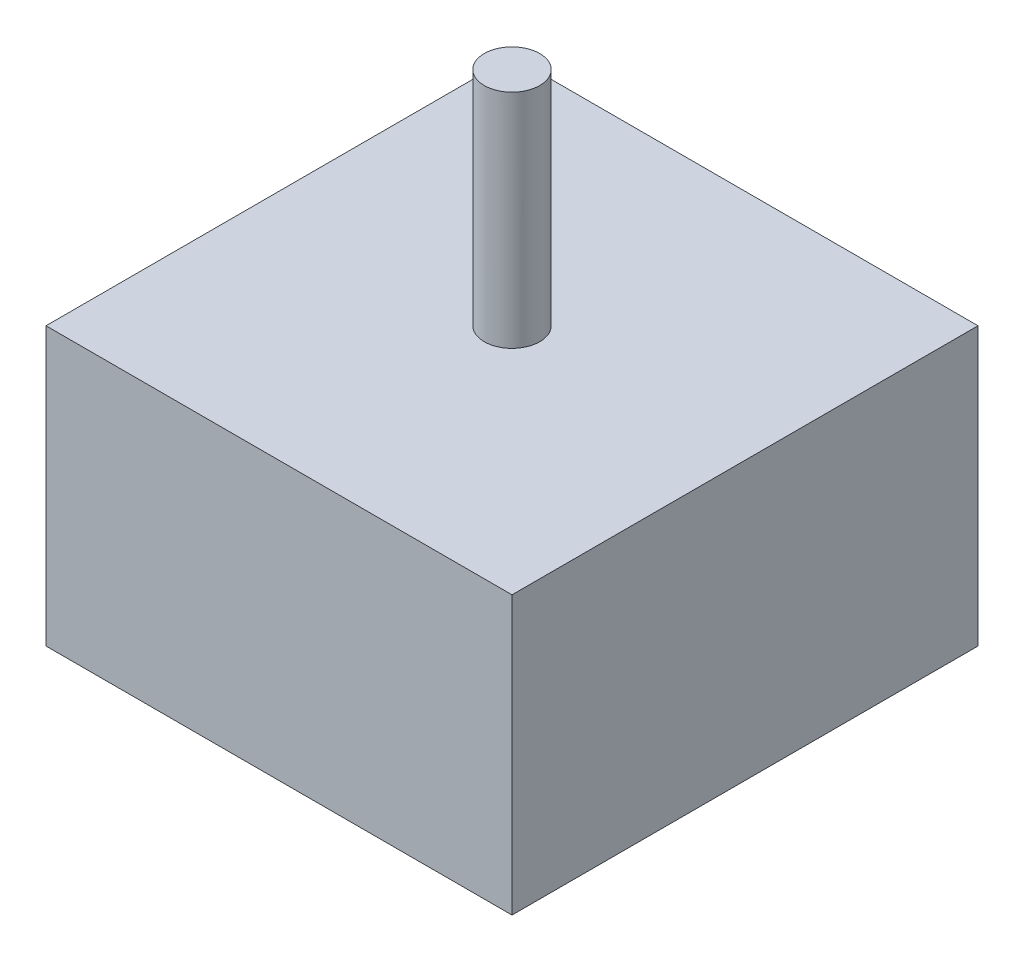
SolidWorks part; units mm, degrees
ref_plane "Front Plane" through (0, 0, 0) normal (0, 0, 1) x (1, 0, 0)
ref_plane "Top Plane" through (0, 0, 0) normal (0, 1, 0) x (1, 0, 0)
ref_plane "Right Plane" through (0, 0, 0) normal (1, 0, 0) x (0, 0, -1)
sketch "Sketch1" plane through (0, 0, 0) normal (0, 1, 0) x (1, 0, 0)
  line L1 (-21, -21) -> (21, -21)
  line L2 (-21, -21) -> (-21, 21)
  line L3 (-21, 21) -> (21, 21)
  line L4 (21, -21) -> (21, 21)
  line L5 (-21, -21) -> (21, 21) construction
  line L6 (-21, 21) -> (21, -21) construction
  point P0 (0, 0)
  dimension "D1" = 42
  dimension "D2" = 42
extrude "Boss-Extrude1" add sketch "Sketch1" along normal blind 25
sketch "Sketch2" plane through (0, 25, 0) normal (0, 1, 0) x (1, 0, 0)
  circle A0 centre (0, 0) radius 2.5
  dimension "D1" = 5
extrude "Boss-Extrude2" add sketch "Sketch2" along normal blind 20
